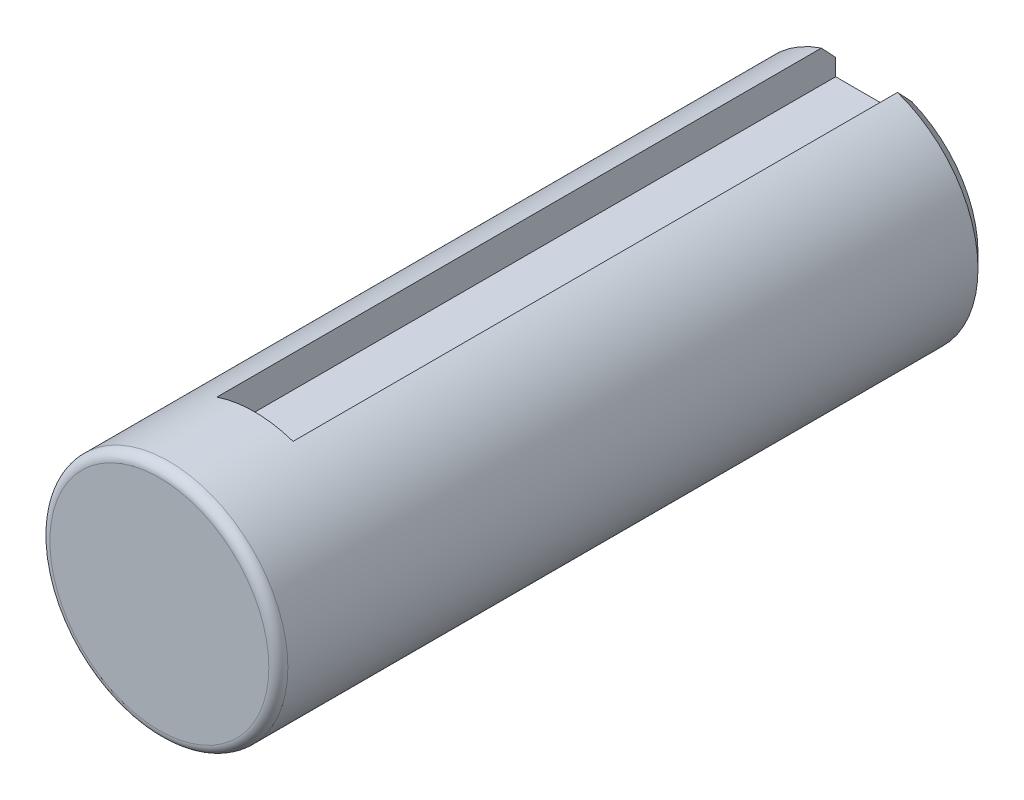
SolidWorks part; units mm, degrees
ref_plane "Front Plane" through (0, 0, 0) normal (0, 0, 1) x (1, 0, 0)
ref_plane "Top Plane" through (0, 0, 0) normal (0, 1, 0) x (1, 0, 0)
ref_plane "Right Plane" through (0, 0, 0) normal (1, 0, 0) x (0, 0, -1)
sketch "Sketch1" plane through (0, 0, 0) normal (0, 0, 1) x (1, 0, 0)
  line L0 (0, 0) -> (0, 16898.8852) construction
  line L1 (0, 0) -> (16898.8852, 0) construction
  circle A0 centre (0, 0) radius 12.5
  dimension "D1" = 25
extrude "Boss-Extrude1" add sketch "Sketch1" along normal blind 75
sketch "Sketch2" plane through (0, 0, 0) normal (0, 0, -1) x (-1, 0, 0)
  line L0 (0, 0) -> (0, 50000) construction
  line L1 (-4.0459, 12.5) -> (-4.0459, 8.5)
  line L2 (-4.0459, 8.5) -> (3.9541, 8.5)
  line L3 (3.9541, 8.5) -> (3.9541, 12.5)
  line L4 (-4.0459, 12.5) -> (3.9541, 12.5)
  circle A1 centre (0, 0) radius 12.5 construction
  circle A2 centre (0, 0) radius 12.5
  circle M7 centre (0, 0) radius 12.5
  dimension "D1" = 8
  dimension "D2" = 4
extrude "Cut-Extrude1" cut sketch "Sketch2" against normal blind 65 contours L2 L0 L1 M7 | L0 L2 L3 M7
chamfer "Chamfer1" distance 1.5 angle 45 1 edges at (-0.0484, -12.4999, 0)
fillet "Fillet1" radius 3 1 edges at (0.0459, 8.5, 65)
fillet "Fillet2" radius 1 1 edges at (12.5, 0, 75)
